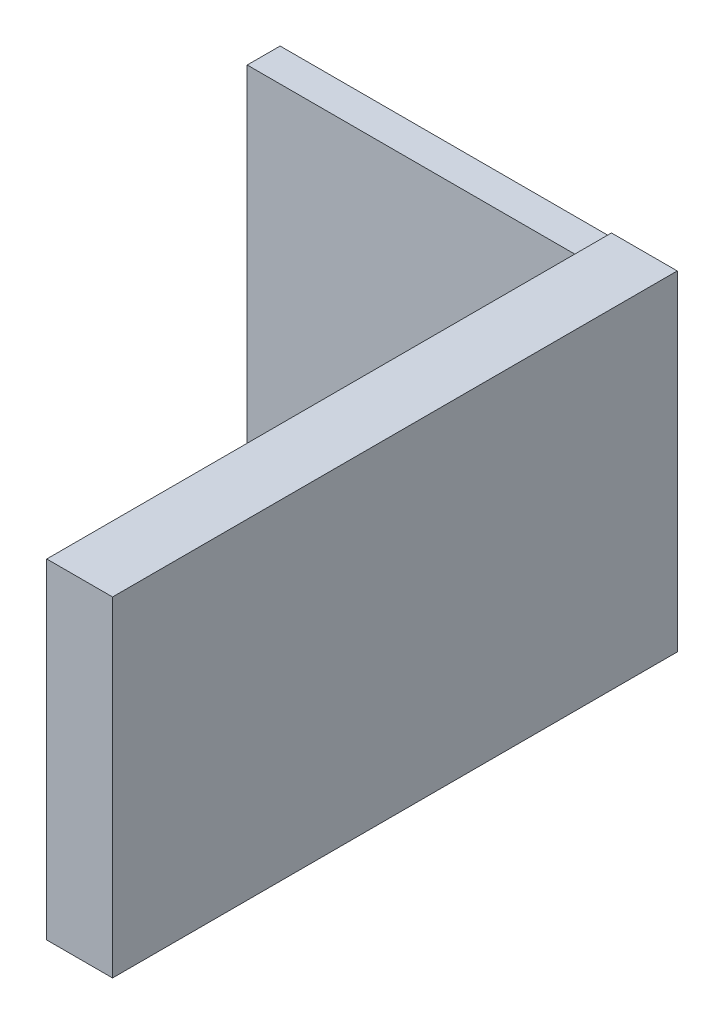
SolidWorks part; units mm, degrees
ref_plane "Front Plane" through (0, 0, 0) normal (0, 0, 1) x (1, 0, 0)
ref_plane "Top Plane" through (0, 0, 0) normal (0, 1, 0) x (1, 0, 0)
ref_plane "Right Plane" through (0, 0, 0) normal (1, 0, 0) x (0, 0, -1)
sketch "Sketch1" plane through (0, 0, 0) normal (0, 0, 1) x (1, 0, 0)
  line L1 (-18.9738, 1.0476) -> (-8.9738, 1.0476)
  line L2 (-18.9738, 1.0476) -> (-18.9738, -8.9524)
  line L3 (-18.9738, -8.9524) -> (-8.9738, -8.9524)
  line L4 (-8.9738, 1.0476) -> (-8.9738, -8.9524)
  line L5 (-18.9738, 1.0476) -> (-8.9738, -8.9524) construction
  line L6 (-18.9738, -8.9524) -> (-8.9738, 1.0476) construction
  point P0 (-13.9738, -3.9524)
extrude "Boss-Extrude1" add sketch "Sketch1" along normal blind 1
ref_plane "Plane1" through (-8.9738, 0, 0) normal (1, 0, 0) x (0, 0, -1)
sketch "Sketch2" plane through (-8.9738, 0, 0) normal (1, 0, 0) x (0, 0, -1)
  line L1 (0.0709, 1.0914) -> (-17.0933, 1.0914)
  line L2 (0.0709, 1.0914) -> (0.0709, -8.9387)
  line L3 (0.0709, -8.9387) -> (-17.0933, -8.9387)
  line L4 (-17.0933, 1.0914) -> (-17.0933, -8.9387)
extrude "Boss-Extrude3" add sketch "Sketch2" along normal blind 2 contours L4 L3 L2 L1
